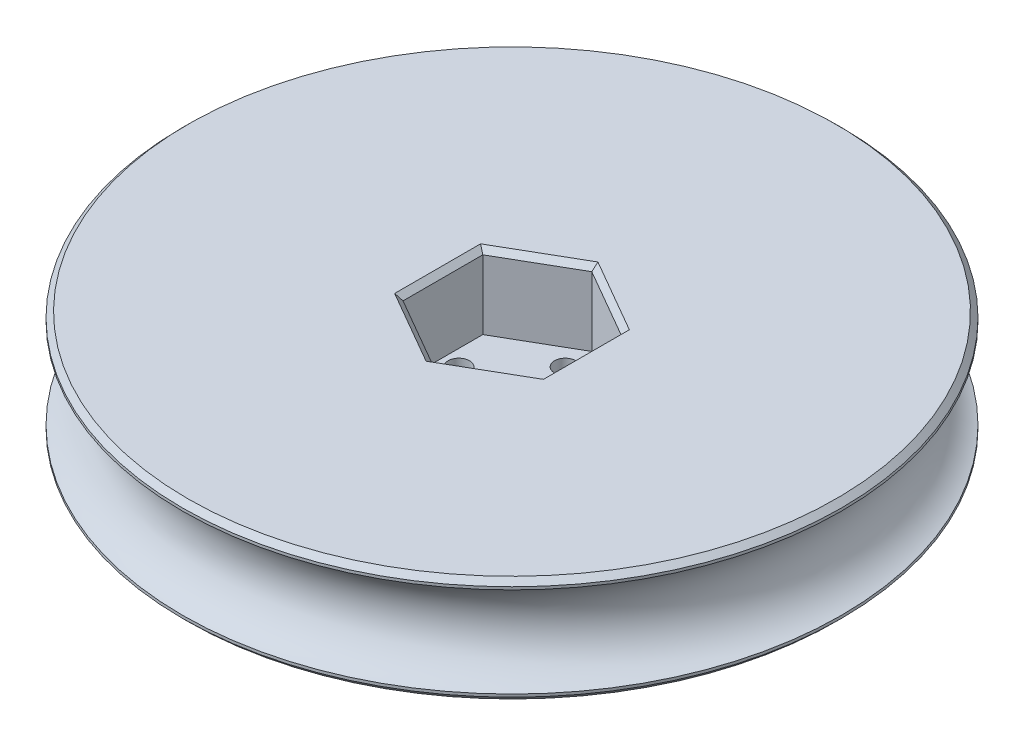
SolidWorks part; units mm, degrees
ref_plane "Спереди" through (0, 0, 0) normal (0, 0, 1) x (1, 0, 0)
ref_plane "Сверху" through (0, 0, 0) normal (0, 1, 0) x (1, 0, 0)
ref_plane "Справа" through (0, 0, 0) normal (1, 0, 0) x (0, 0, -1)
sketch "Эскиз1" plane through (0, 0, 0) normal (0, 1, 0) x (1, 0, 0)
  circle A0 centre (0, 0) radius 62
  dimension "D1" = 124
extrude "Бобышка-Вытянуть1" add sketch "Эскиз1" along normal blind 20
sketch "Эскиз3" plane through (0, 0, 0) normal (0, 0, 1) x (1, 0, 0)
  line L0 (0, 0) -> (0, 20) construction
  line L1 (62, 20) -> (-62, 20) construction
  line L2 (0, 20) -> (0, 10) construction
  line L3 (0, 10) -> (-84.2443, 10) construction
  line L9 (-56, -6.4426) -> (-56, 31.0537) construction
  circle A2 centre (-65, 10) radius 9
  dimension "D1" = 56
  dimension "D2" = 18
revolve "Вырез-Повернуть2" cut sketch "Эскиз3" angle 360 about L0
chamfer "Фаска3" distance 1 angle 45 1 edges at (0, 0, 62)
sketch "Эскиз5" plane through (0, 20, 0) normal (0, 1, 0) x (1, 0, 0)
  line L1 (0, 15.0111) -> (-13, 7.5056)
  line L2 (-13, 7.5056) -> (-13, -7.5056)
  line L3 (-13, -7.5056) -> (0, -15.0111)
  line L4 (0, -15.0111) -> (13, -7.5056)
  line L5 (13, -7.5056) -> (13, 7.5056)
  line L6 (13, 7.5056) -> (0, 15.0111)
  circle A1 centre (0, 0) radius 13 construction
  dimension "D1" = 26
extrude "Вырез-Вытянуть2" cut sketch "Эскиз5" against normal blind 14
sketch "Эскиз6" plane through (0, 20, 0) normal (0, 1, 0) x (1, 0, 0)
  line L0 (0, 35.5494) -> (0, 0) construction
  line L1 (0, 0) -> (32.442, 0) construction
  circle A0 centre (0, 10) radius 2
  circle A1 centre (10, 0) radius 2
  circle A2 centre (0, -10) radius 2
  circle A3 centre (-10, 0) radius 2
  point P15 (0, 0)
  dimension "D1" = 10
  dimension "D2" = 4
extrude "Вырез-Вытянуть3" cut sketch "Эскиз6" against normal through all contours A0
chamfer "Фаска2" distance 1 angle 45 7 edges at (0, 20, 62) (-6.5, 20, -11.2583) (-13, 20, 0) (-6.5, 20, 11.2583) (6.5, 20, 11.2583) (13, 20, 0) (6.5, 20, -11.2583)
sketch "Эскиз7" plane through (0, 0, 0) normal (0, -1, 0) x (1, 0, 0)
  line L0 (0, 27.6772) -> (0, 0) construction
  line L1 (0, 0) -> (27.5529, 0) construction
  circle A0 centre (0, 10) radius 4
  circle A1 centre (10, 0) radius 4
  circle A2 centre (0, -10) radius 4
  circle A3 centre (-10, 0) radius 4
  point P15 (0, 0)
  dimension "D1" = 10
  dimension "D2" = 4
extrude "Вырез-Вытянуть4" [suppressed] cut sketch "Эскиз7" against normal blind 4 contours A0
chamfer "Фаска4" distance 2 angle 45 4 edges at (-10, 0, 2) (0, 0, -8) (10, 0, 2) (0, 0, 12)
